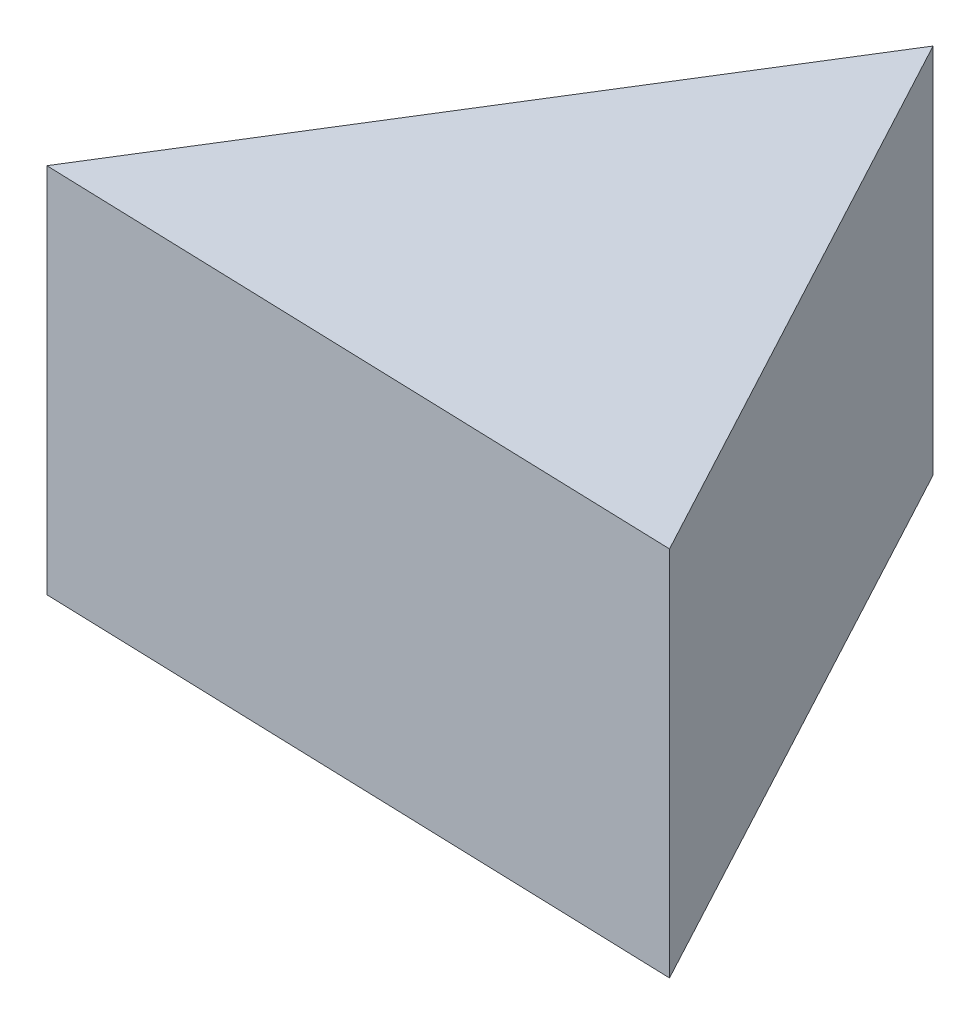
SolidWorks part; units mm, degrees
ref_plane "Front Plane" through (0, 0, 0) normal (0, 0, 1) x (1, 0, 0)
ref_plane "Top Plane" through (0, 0, 0) normal (0, 1, 0) x (1, 0, 0)
ref_plane "Right Plane" through (0, 0, 0) normal (1, 0, 0) x (0, 0, -1)
sketch "Sketch1" plane through (0, 0, 0) normal (0, 1, 0) x (1, 0, 0)
  line L1 (-19.6054, 0) -> (-35.9563, 30.5393)
  line L2 (-35.9563, 30.5393) -> (-54.2287, 1.1094)
  line L3 (-54.2287, 1.1094) -> (-19.6054, 0)
  circle A0 centre (-36.5968, 10.5496) radius 10 construction
  dimension "D1" = 20
extrude "Boss-Extrude1" add sketch "Sketch1" against normal blind 20
